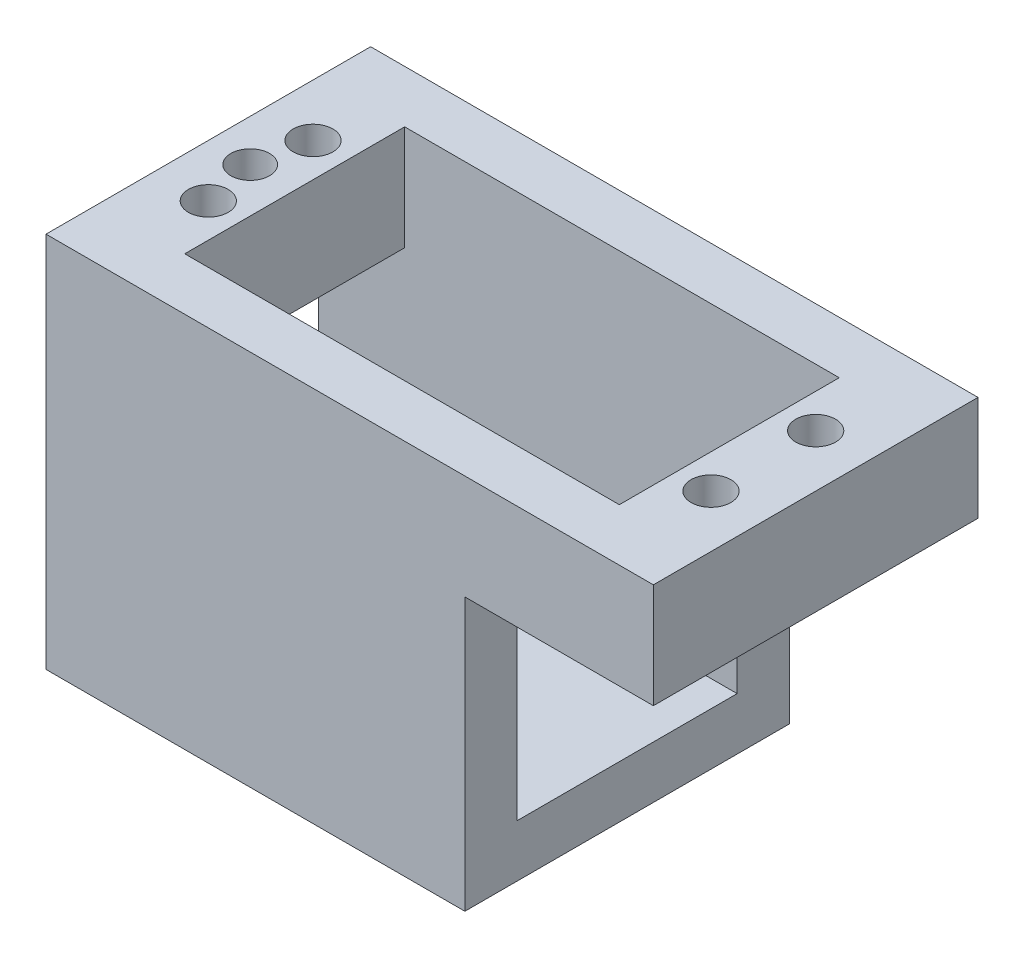
SolidWorks part; units mm, degrees
ref_plane "Alzado" through (0, 0, 0) normal (0, 0, 1) x (1, 0, 0)
ref_plane "Planta" through (0, 0, 0) normal (0, 1, 0) x (1, 0, 0)
ref_plane "Vista lateral" through (0, 0, 0) normal (1, 0, 0) x (0, 0, -1)
sketch "Croquis1" plane through (0, 0, 0) normal (0, 1, 0) x (1, 0, 0)
  line L1 (-24, 5) -> (24, 5) construction
  line L2 (-24, 5) -> (-24, -5) construction
  line L3 (-24, -5) -> (24, -5) construction
  line L4 (24, 5) -> (24, -5) construction
  line L5 (-24, 5) -> (24, -5) construction
  line L6 (-24, -5) -> (24, 5) construction
  line L7 (-20.75, 10.5) -> (20.75, 10.5)
  line L8 (-20.75, 10.5) -> (-20.75, -10.5)
  line L9 (-20.75, -10.5) -> (20.75, -10.5)
  line L10 (20.75, 10.5) -> (20.75, -10.5)
  line L11 (-20.75, 10.5) -> (20.75, -10.5) construction
  line L12 (-20.75, -10.5) -> (20.75, 10.5) construction
  line L13 (-29, 15.5) -> (29, 15.5)
  line L14 (-29, 15.5) -> (-29, -15.5)
  line L15 (-29, -15.5) -> (29, -15.5)
  line L16 (29, 15.5) -> (29, -15.5)
  line L17 (-29, 15.5) -> (29, -15.5) construction
  line L18 (-29, -15.5) -> (29, 15.5) construction
  circle A0 centre (-24, -5) radius 1.9
  circle A1 centre (24, -5) radius 1.9
  circle A2 centre (24, 5) radius 1.9
  circle A3 centre (-24, 5) radius 1.9
  point P0 (0, 0)
  point P10 (0, 0)
  point P15 (0, 0)
  dimension "D3" = 3.8
  dimension "D1" = 48
  dimension "D2" = 10
  dimension "D4" = 41.5
  dimension "D5" = 21
  dimension "D6" = 31
  dimension "D7" = 58
extrude "Saliente-Extruir1" add sketch "Croquis1" along normal blind 10
sketch "Croquis2" plane through (0, 0, 0) normal (0, -1, 0) x (1, 0, 0)
  line L0 (-29, 15.5) -> (29, 15.5) construction
  line L1 (-29, 15.5) -> (11, 15.5)
  line L2 (-29, 15.5) -> (-29, 10.5)
  line L3 (-29, 10.5) -> (11, 10.5)
  line L4 (11, 15.5) -> (11, 10.5)
  line L5 (-20.75, 10.5) -> (20.75, 10.5) construction
  line L7 (20.75, -10.5) -> (-20.75, -10.5) construction
  line L9 (-29, -10.5) -> (11, -10.5)
  line L10 (-29, -10.5) -> (-29, -15.5)
  line L11 (-29, -15.5) -> (11, -15.5)
  line L12 (11, -10.5) -> (11, -15.5)
  line L13 (29, -15.5) -> (-29, -15.5) construction
  point P8 (-29, 15.5)
  dimension "D1" = 40
extrude "Saliente-Extruir2" add sketch "Croquis2" along normal blind 21
sketch "Croquis3" plane through (0, -21, 0) normal (0, -1, 0) x (1, 0, 0)
  line L1 (-29, 15.5) -> (11, 15.5)
  line L2 (-29, 15.5) -> (-29, -15.5)
  line L3 (-29, -15.5) -> (11, -15.5)
  line L4 (11, 15.5) -> (11, -15.5)
extrude "Saliente-Extruir3" add sketch "Croquis3" along normal blind 5
sketch "Croquis4" plane through (0, -26, 0) normal (0, -1, 0) x (1, 0, 0)
  line L0 (0, 0) -> (-29, 0) construction
  line L1 (-29, 15.5) -> (-29, -15.5) construction
  line L2 (-15, 0) -> (-17, 0) construction
  line L3 (-29, 4) -> (-5, 4)
  line L4 (-29, 4) -> (-29, -4)
  line L5 (-29, -4) -> (-5, -4)
  line L6 (-5, 4) -> (-5, -4)
  line L7 (-29, 4) -> (-5, -4) construction
  line L8 (-29, -4) -> (-5, 4) construction
  circle A0 centre (-25, 0) radius 1.85
  circle A1 centre (-15, 0) radius 1.85
  point P5 (-17, 0)
  dimension "D1" = 3.7
  dimension "D4" = 10
  dimension "D5" = 4
  dimension "D2" = 8
  dimension "D3" = 24
extrude "Saliente-Extruir4" add sketch "Croquis4" along normal blind 7.2
sketch "Croquis5" plane through (0, -33.2, 0) normal (0, -1, 0) x (1, 0, 0)
  circle A0 centre (-25, 0) radius 1.85
  circle A1 centre (-15, 0) radius 1.85
  circle A2 centre (-25, 0) radius 1.85 construction
extrude "Cortar-Extruir1" cut sketch "Croquis5" against normal through all
sketch "Croquis6" plane through (0, -21, 0) normal (0, 1, 0) x (1, 0, 0)
  circle A0 centre (-25, 0) radius 3
  circle A1 centre (-15, 0) radius 3
  dimension "D1" = 6
extrude "Cortar-Extruir2" cut sketch "Croquis6" against normal blind 3.5
sketch "Croquis7" plane through (0, -21, 0) normal (0, 1, 0) x (1, 0, 0)
  circle A0 centre (-25, 0) radius 3.05
  circle A1 centre (-15, 0) radius 3.05
  dimension "D1" = 6.1
extrude "Saliente-Extruir5" add sketch "Croquis7" against normal blind 0.2 separate body
